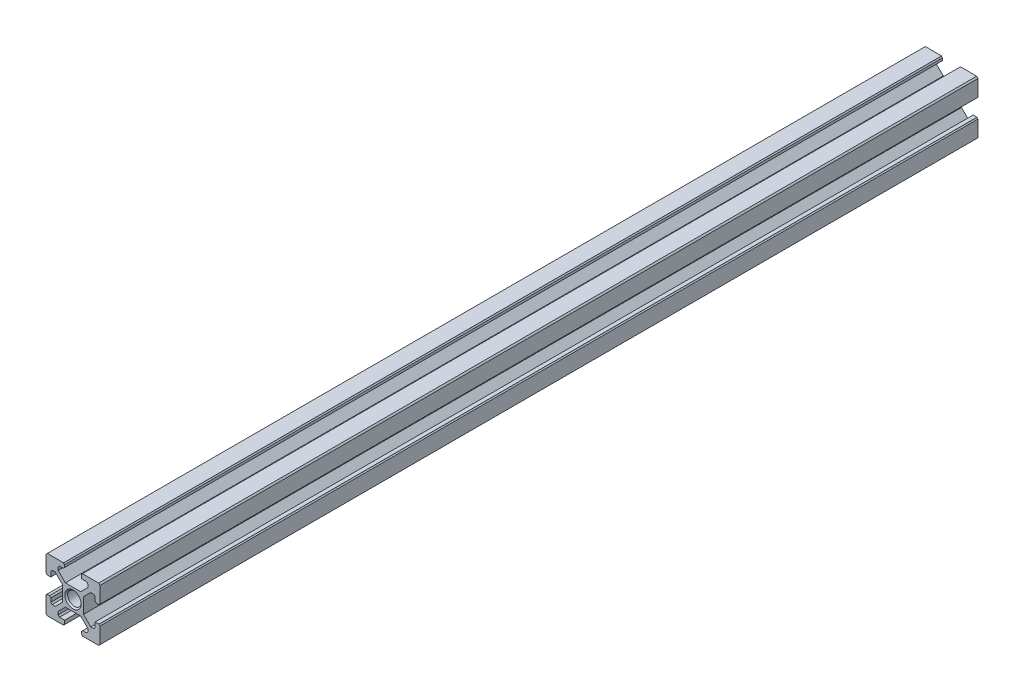
SolidWorks part; units mm, degrees
ref_plane "Front Plane" through (0, 0, 0) normal (0, 0, 1) x (1, 0, 0)
ref_plane "Top Plane" through (0, 0, 0) normal (0, 1, 0) x (1, 0, 0)
ref_plane "Right Plane" through (0, 0, 0) normal (1, 0, 0) x (0, 0, -1)
sketch "Sketch1" plane through (0, 0, 0) normal (0, 0, 1) x (1, 0, 0)
  line L0 (0, 10.7337) -> (0, 0.7337) construction
  line L1 (-9.5, 10) -> (-3.4865, 10)
  line L2 (-10, 9.5) -> (-10, 3.4865)
  line L3 (-9.5, -10) -> (-3.4865, -10)
  line L4 (10, 9.5) -> (10, 3.4865)
  line L5 (-9.75, 9.75) -> (9.75, -9.75) construction
  line L6 (-9.75, -9.75) -> (10, 10) construction
  line L7 (0, 0) -> (-10, 0) construction
  line L8 (3.1, 9.6135) -> (3.1, 8.2)
  line L9 (3.1, 8.2) -> (5, 8.2)
  line L10 (5.5, 7.7) -> (5.5, 6.5607)
  line L11 (5.5, 6.5607) -> (2.8393, 3.9)
  line L12 (2.8393, 3.9) -> (0, 3.9)
  line L13 (3.9, 2.8393) -> (3.9, 0)
  line L14 (6.5607, 5.5) -> (3.9, 2.8393)
  line L15 (9.6135, 3.1) -> (8.7, 3.1)
  line L16 (8.2, 3.6) -> (8.2, 5)
  line L17 (7.7, 5.5) -> (6.5607, 5.5)
  line L18 (3.4865, 10) -> (9.5, 10)
  line L19 (10, -3.4865) -> (10, -9.5)
  line L20 (5, 8.2) -> (5.5, 7.7)
  line L21 (8.2, 5) -> (7.7, 5.5)
  line L22 (9.5, 10) -> (10, 9.5)
  line L23 (8.7, 3.1) -> (8.2, 3.6)
  line L24 (3.9, -2.8393) -> (3.9, 0)
  line L25 (6.5607, -5.5) -> (3.9, -2.8393)
  line L26 (7.7, -5.5) -> (6.5607, -5.5)
  line L27 (8.2, -5) -> (7.7, -5.5)
  line L28 (8.2, -3.1) -> (8.2, -5)
  line L29 (9.6135, -3.1) -> (8.2, -3.1)
  line L30 (10, -3.4865) -> (10, -9.5)
  line L31 (10, -9.5) -> (9.5, -10)
  line L32 (9.5, -10) -> (3.4865, -10)
  line L33 (3.1, -9.6135) -> (3.1, -8.7)
  line L34 (3.1, -8.7) -> (3.6, -8.2)
  line L35 (3.6, -8.2) -> (5, -8.2)
  line L36 (5, -8.2) -> (5.5, -7.7)
  line L37 (5.5, -7.7) -> (5.5, -6.5607)
  line L38 (5.5, -6.5607) -> (2.8393, -3.9)
  line L39 (2.8393, -3.9) -> (0, -3.9)
  line L40 (-2.8393, -3.9) -> (0, -3.9)
  line L41 (-5.5, -6.5607) -> (-2.8393, -3.9)
  line L42 (-5.5, -7.7) -> (-5.5, -6.5607)
  line L43 (-5, -8.2) -> (-5.5, -7.7)
  line L44 (-3.1, -8.2) -> (-5, -8.2)
  line L45 (-3.1, -9.6135) -> (-3.1, -8.2)
  line L46 (-3.4865, -10) -> (-9.5, -10)
  line L47 (-9.5, -10) -> (-10, -9.5)
  line L48 (-10, -9.5) -> (-10, -3.4865)
  line L49 (-9.6135, -3.1) -> (-8.7, -3.1)
  line L50 (-8.7, -3.1) -> (-8.2, -3.6)
  line L51 (-8.2, -3.6) -> (-8.2, -5)
  line L52 (-8.2, -5) -> (-7.7, -5.5)
  line L53 (-7.7, -5.5) -> (-6.5607, -5.5)
  line L54 (-6.5607, -5.5) -> (-3.9, -2.8393)
  line L55 (-3.9, -2.8393) -> (-3.9, 0)
  line L56 (-3.9, 2.8393) -> (-3.9, 0)
  line L57 (-6.5607, 5.5) -> (-3.9, 2.8393)
  line L58 (-7.7, 5.5) -> (-6.5607, 5.5)
  line L59 (-8.2, 5) -> (-7.7, 5.5)
  line L60 (-8.2, 3.1) -> (-8.2, 5)
  line L61 (-9.6135, 3.1) -> (-8.2, 3.1)
  line L62 (-10, 3.4865) -> (-10, 9.5)
  line L63 (-10, 9.5) -> (-9.5, 10)
  line L64 (-9.5, 10) -> (-3.4865, 10)
  line L65 (-3.1, 9.6135) -> (-3.1, 8.7)
  line L66 (-3.1, 8.7) -> (-3.6, 8.2)
  line L67 (-3.6, 8.2) -> (-5, 8.2)
  line L68 (-5, 8.2) -> (-5.5, 7.7)
  line L69 (-5.5, 7.7) -> (-5.5, 6.5607)
  line L70 (-5.5, 6.5607) -> (-2.8393, 3.9)
  line L71 (-2.8393, 3.9) -> (0, 3.9)
  line L72 (3.4865, -10) -> (9.5, -10)
  line L73 (-10, -3.4865) -> (-10, -9.5)
  arc A0 (3.1, 9.6135) -> (3.4865, 10) centre (3.1, 10) ccw
  arc A1 (9.6135, 3.1) -> (10, 3.4865) centre (10, 3.1) cw
  arc A2 (9.6135, -3.1) -> (10, -3.4865) centre (10, -3.1) ccw
  arc A3 (3.1, -9.6135) -> (3.4865, -10) centre (3.1, -10) cw
  arc A4 (-3.1, -9.6135) -> (-3.4865, -10) centre (-3.1, -10) ccw
  arc A5 (-9.6135, -3.1) -> (-10, -3.4865) centre (-10, -3.1) cw
  arc A6 (-9.6135, 3.1) -> (-10, 3.4865) centre (-10, 3.1) ccw
  arc A7 (-3.1, 9.6135) -> (-3.4865, 10) centre (-3.1, 10) cw
  point P0 (0, 0)
  point P13 (5.5, 8.2)
  point P17 (3.1, 8.9068)
  point P22 (8.2, 3.1)
  point P23 (8.2, 5.5)
  point P103 (0, 0)
  dimension "D3" = 1.8
  dimension "D4" = 6.1
  dimension "D5" = 11
  dimension "D6" = 6.2
  dimension "D7" = 1.5
extrude "Boss-Extrude1" add sketch "Sketch1" along normal blind 325 contours L65 A7 L1 L63 L2 A6 L61 L60 L59 L58 L57 L56 L55 L54 L53 L52 L51 L50 L49 A5 L48 L47 L3 A4 L45 L44 L43 L42 L41 L40 L39 L38 L37 L36 L35 L34 L33 A3 L32 L31 L19 A2 L29 L28 L27 L26 L25 L24 L13 L14 L17
hole_wizard "M6x1.0 Tapped Hole1" positions "3DSketch1" profile "Sketch2" tap size "M6x1.0" standard "ANSI Metric"
sketch3d "3DSketch1"
  line L0 (3.9, -2.8393, 325) -> (3.9, 2.8393, 325) construction
  line L1 (2.8393, 3.9, 325) -> (-2.8393, 3.9, 325) construction
  point P0 (0, 0, 0)
  point P3 (0, 0, 0)
  point P5 (0, 0, 0)
  point P7 (0.9996, -8.1302, 0)
  point P9 (0, 0, 0)
  point P11 (0, 0, 325)
  dimension "D1" = 3.9
  dimension "D2" = 3.9
sketch "Sketch2" plane through (0, 0, 325) normal (1, 0, 0) x (0, -1, 0)
  line L0 (0, 0) -> (0, 30)
  line L1 (0, 30) -> (2.5, 28.4978)
  line L2 (2.5, 28.4978) -> (2.5, 0.525)
  line L3 (2.5, 0.525) -> (3.025, 0)
  line L5 (3.025, 0) -> (0, 0)
  line L6 (-2.5, 0.525) -> (-3.025, 0) construction
  line L10 (0, 30) -> (-2.5, 28.4978) construction
  line L11 (0, -6.35) -> (0, 107.95) construction
  dimension "Tap Drill Dia." = 5
  dimension "Tap Drill Depth" = 30
  dimension "Near C'Sink Dia." = 6.05
  dimension "Near C'Sink Angle" = 90
  dimension "Drill Angle" = 118
cosmetic thread "Hole Thread6" parameters "D1"=12, "D2"=6
hole_wizard "M6x1.0 Tapped Hole2" positions "3DSketch2" profile "Sketch3" tap size "M6x1.0" standard "ANSI Metric"
sketch3d "3DSketch2"
  line L0 (2.8393, 3.9, 0) -> (-2.8393, 3.9, 0) construction
  line L1 (3.9, -2.8393, 0) -> (3.9, 2.8393, 0) construction
  point P3 (0, 0, 0)
  dimension "D1" = 3.9
  dimension "D2" = 3.9
sketch "Sketch3" plane through (0, 0, 0) normal (1, 0, 0) x (0, 1, 0)
  line L0 (0, 0) -> (0, 30)
  line L1 (0, 30) -> (2.5, 28.4978)
  line L2 (2.5, 28.4978) -> (2.5, 0.525)
  line L3 (2.5, 0.525) -> (3.025, 0)
  line L5 (3.025, 0) -> (0, 0)
  line L6 (-2.5, 0.525) -> (-3.025, 0) construction
  line L10 (0, 30) -> (-2.5, 28.4978) construction
  line L11 (0, -6.35) -> (0, 107.95) construction
  dimension "Tap Drill Dia." = 5
  dimension "Tap Drill Depth" = 30
  dimension "Near C'Sink Dia." = 6.05
  dimension "Near C'Sink Angle" = 90
  dimension "Drill Angle" = 118
cosmetic thread "Hole Thread7" parameters "D1"=12, "D2"=6
